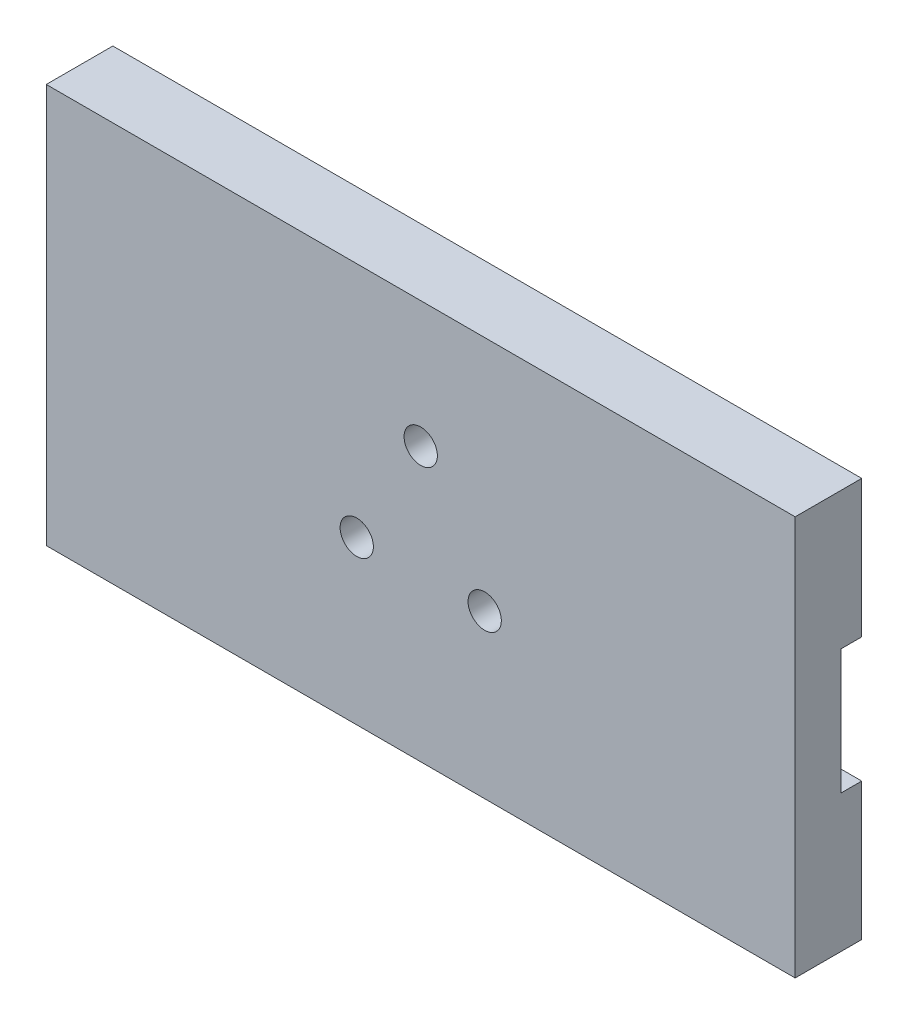
SolidWorks part; units mm, degrees
material "3d打印 35%"
ref_plane "前视基准面" through (0, 0, 0) normal (0, 0, 1) x (1, 0, 0)
ref_plane "上视基准面" through (0, 0, 0) normal (0, 1, 0) x (1, 0, 0)
ref_plane "右视基准面" through (0, 0, 0) normal (1, 0, 0) x (0, 0, -1)
sketch "草图1" plane through (0, 0, 0) normal (0, 0, 1) x (1, 0, 0)
  line L1 (-45, 24) -> (45, 24)
  line L2 (-45, 24) -> (-45, -24)
  line L3 (-45, -24) -> (45, -24)
  line L4 (45, 24) -> (45, -24)
  line L5 (-45, 24) -> (45, -24) construction
  line L6 (-45, -24) -> (45, 24) construction
  point P0 (0, 0)
  dimension "D1" = 90
  dimension "D2" = 48
extrude "凸台-拉伸1" add sketch "草图1" along normal blind 8 contours L1 L4 L3 L2
sketch "草图2" plane through (0, 0, 0) normal (0, 0, -1) x (-1, 0, 0)
  line L1 (-45, 24) -> (-37, 24)
  line L2 (-45, 24) -> (-45, 7.5)
  line L3 (-45, 7.5) -> (-37, 7.5)
  line L4 (-37, 24) -> (-37, 7.5)
ref_plane "基准面4" through (0, 0, 0) normal (1, 0, 0) x (0, 0, -1)
ref_plane "基准面5" through (0, 0, 0) normal (0, 1, 0) x (1, 0, 0)
sketch "草图4" plane through (0, 0, 8) normal (0, 0, 1) x (1, 0, 0)
  line L0 (0, -4.4) -> (0, 4.4) construction
  circle A0 centre (0, 8.85) radius 2
  dimension "D1" = 8.85
  dimension "D2" = 4
sketch "草图6" plane through (0, 0, 0) normal (0, 0, -1) x (-1, 0, 0)
  line L0 (-45, 24) -> (-37, 24) construction
  line L1 (-45, 24) -> (-45, 7.5) construction
  circle A0 centre (-41, 21) radius 1.8
  dimension "D1" = 3
  dimension "D2" = 4
extrude "切除-拉伸4" cut sketch "草图6" against normal blind 3
mirror "镜向5" about plane through (0, 0, 0) normal (0, 1, 0) of "切除-拉伸4"
mirror "镜向6" about plane through (0, 0, 0) normal (1, 0, 0) of "镜向5", "切除-拉伸4"
sketch "草图7" plane through (0, 0, 0) normal (0, 0, -1) x (-1, 0, 0)
  line L0 (4.4, 0) -> (-4.4, 0) construction
  line L1 (-53.0518, 7.5) -> (-37.0518, 7.5)
  line L2 (-53.0518, 7.5) -> (-53.0518, -7.5)
  line L3 (-53.0518, -7.5) -> (-37.0518, -7.5)
  line L4 (-37.0518, 7.5) -> (-37.0518, -7.5)
  line L5 (-53.0518, 7.5) -> (-37.0518, -7.5) construction
  line L6 (-53.0518, -7.5) -> (-37.0518, 7.5) construction
  point P0 (-45.0518, 0)
  dimension "D1" = 15
  dimension "D2" = 16
extrude "切除-拉伸5" cut sketch "草图7" against normal blind 2.5
mirror "镜向7" about plane through (0, 0, 0) normal (1, 0, 0) of "切除-拉伸5"
extrude "切除-拉伸6" cut sketch "草图4" against normal blind 10
pattern_circular "阵列(圆周)1" count 3 every 120 about axis through (0, -0.0276, 0) along (0, 0, 1) of "切除-拉伸6"
